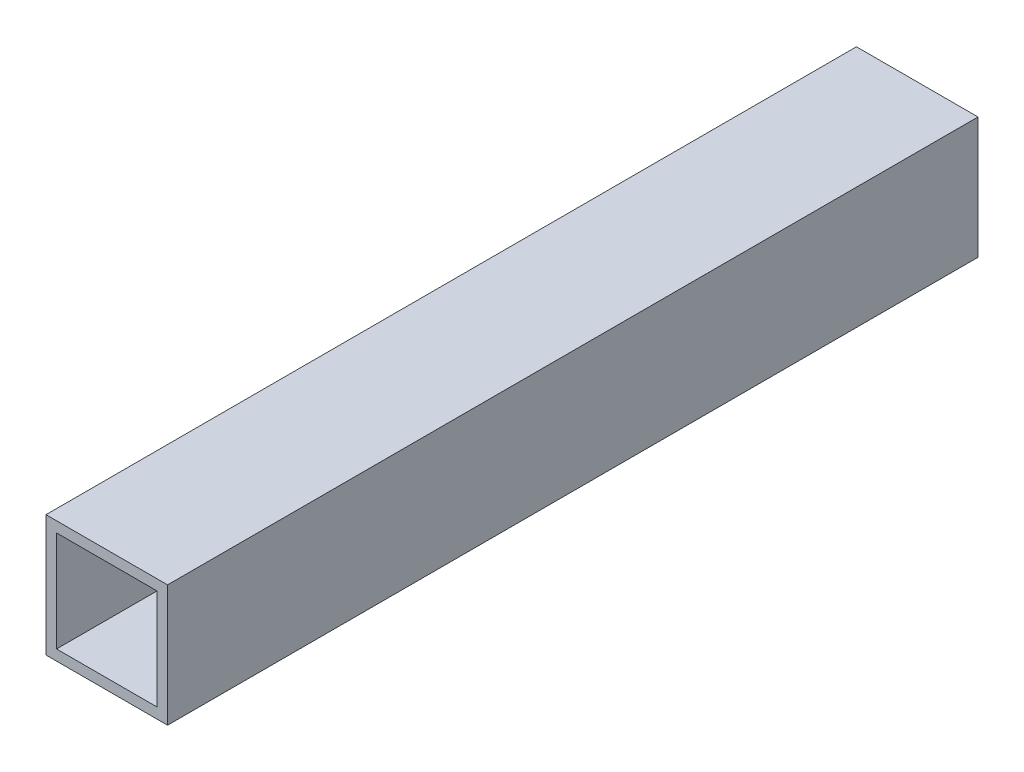
SolidWorks part; units mm, degrees
material "Plain Carbon Steel"
ref_plane "Front Plane" through (0, 0, 0) normal (0, 0, 1) x (1, 0, 0)
ref_plane "Top Plane" through (0, 0, 0) normal (0, 1, 0) x (1, 0, 0)
ref_plane "Right Plane" through (0, 0, 0) normal (1, 0, 0) x (0, 0, -1)
sketch "Sketch1" plane through (0, 0, 0) normal (0, 0, 1) x (1, 0, 0)
  line L1 (-19.05, -19.05) -> (19.05, -19.05)
  line L2 (-19.05, -19.05) -> (-19.05, 19.05)
  line L3 (-19.05, 19.05) -> (19.05, 19.05)
  line L4 (19.05, -19.05) -> (19.05, 19.05)
  line L5 (-19.05, -19.05) -> (19.05, 19.05) construction
  line L6 (-19.05, 19.05) -> (19.05, -19.05) construction
  line L7 (-15.748, -15.748) -> (15.748, -15.748)
  line L8 (-15.748, -15.748) -> (-15.748, 15.748)
  line L9 (-15.748, 15.748) -> (15.748, 15.748)
  line L10 (15.748, -15.748) -> (15.748, 15.748)
  line L11 (-15.748, -15.748) -> (15.748, 15.748) construction
  line L12 (-15.748, 15.748) -> (15.748, -15.748) construction
  point P0 (0, 0)
  point P6 (0, 0)
  dimension "D1" = 38.1
  dimension "D2" = 3.302
extrude "Extrude1" add sketch "Sketch1" along normal blind 254
sketch "Sketch2" plane through (0, 0, 0) normal (0, 0, -1) x (-1, 0, 0)
  line L0 (0, 15.748) -> (0, -15.748) construction
  line L1 (-15.748, 15.748) -> (15.748, 15.748) construction
  line L2 (15.748, -15.748) -> (-15.748, -15.748) construction
  line L3 (15.748, 0) -> (-15.748, 0) construction
  line L4 (15.748, 15.748) -> (15.748, -15.748) construction
  line L5 (-15.748, -15.748) -> (-15.748, 15.748) construction
  point P12 (0, 0)
